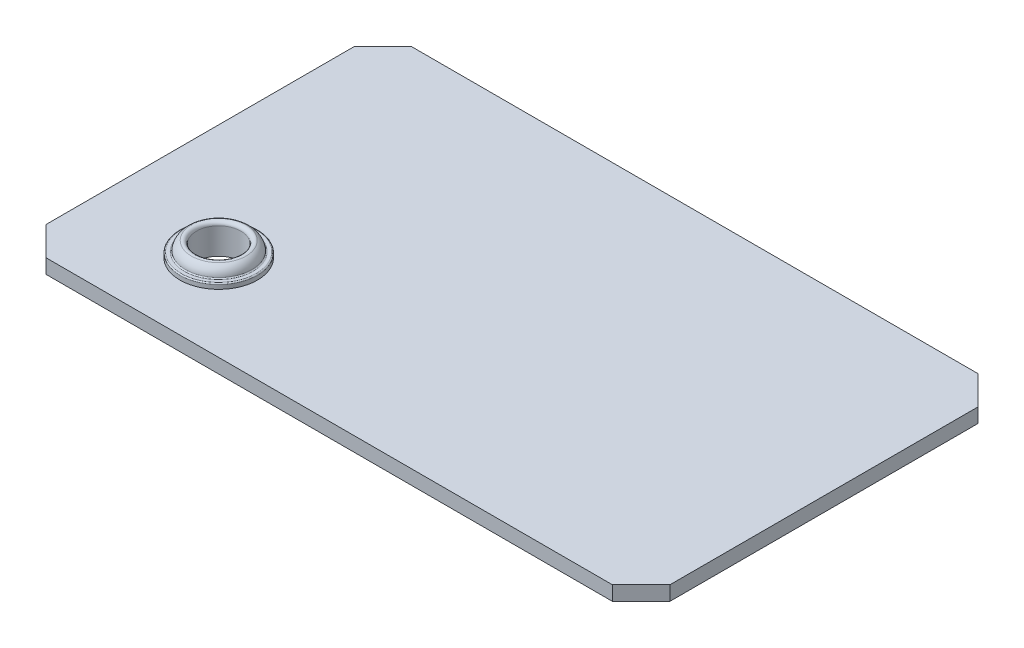
SolidWorks part; units mm, degrees
ref_plane "Front Plane" through (0, 0, 0) normal (0, 0, 1) x (1, 0, 0)
ref_plane "Top Plane" through (0, 0, 0) normal (0, 1, 0) x (1, 0, 0)
ref_plane "Right Plane" through (0, 0, 0) normal (1, 0, 0) x (0, 0, -1)
sketch "Sketch1" plane through (0, 0, 0) normal (0, 1, 0) x (1, 0, 0)
  line L0 (131.2934, 0) -> (137.6434, 6.35)
  line L1 (6.35, 0) -> (131.2934, 0)
  line L2 (0, 6.35) -> (0, 74.3051)
  line L3 (6.35, 80.6551) -> (131.2934, 80.6551)
  line L4 (137.6434, 6.35) -> (137.6434, 74.3051)
  line L5 (137.6434, 74.3051) -> (131.2934, 80.6551)
  line L6 (0, 74.3051) -> (6.35, 80.6551)
  line L7 (6.35, 0) -> (0, 6.35)
  point P0 (0, 0)
  point P1 (137.6434, 80.6551)
  point P2 (0, 80.6551)
  point P3 (137.6434, 0)
  dimension "D3" = 6.35
  dimension "D4" = 6.35
  dimension "D5" = 6.35
  dimension "D6" = 6.35
extrude "Extrude1" add sketch "Sketch1" against normal blind 3.175
ref_plane "Plane1" through (0, 0, -19.05) normal (0, 0, 1) x (1, 0, 0)
sketch "Sketch3" plane through (0, 0, -19.05) normal (0, 0, 1) x (1, 0, 0)
  line L0 (25.4, 0) -> (33.9525, 0)
  line L1 (25.4, 0) -> (25.4, 1.8037)
  line L2 (30.2995, 1.8037) -> (30.2995, 2.6328)
  line L3 (6.35, 0) -> (131.2934, 0) construction
  line L4 (33.9525, 0) -> (33.9525, 0.9046)
  line L5 (33.6985, 1.1586) -> (32.963, 1.1586)
  line L8 (25.4, 1.8037) -> (30.2995, 1.8037)
  arc A0 (32.7101, 1.3885) -> (31.4114, 3.3098) centre (30.2995, 1.1586) ccw
  arc A1 (31.4114, 3.3098) -> (30.2995, 2.6328) centre (31.0615, 2.6328) ccw
  arc A2 (33.9525, 0.9046) -> (33.6985, 1.1586) centre (33.6985, 0.9046) ccw
  arc A3 (32.7101, 1.3885) -> (32.963, 1.1586) centre (32.963, 1.4126) ccw
  dimension "D1" = 0.762
  dimension "D2" = 0.254
  dimension "D3" = 0.254
revolve "Revolve1" add sketch "Sketch3" angle 360 about L1
sketch "Sketch5" plane through (0, 0, 0) normal (0, 1, 0) x (1, 0, 0)
  circle A0 centre (25.4, 19.05) radius 4.8995
extrude "Extrude2" cut sketch "Sketch5" against normal mid plane 13.843
sketch "Sketch6" plane through (0, 0, 0) normal (0, 1, 0) x (1, 0, 0)
  point P0 (50.5907, 58.4758)
  point P1 (77.9013, 31.642)
  point P2 (111.2547, 53.8846)
